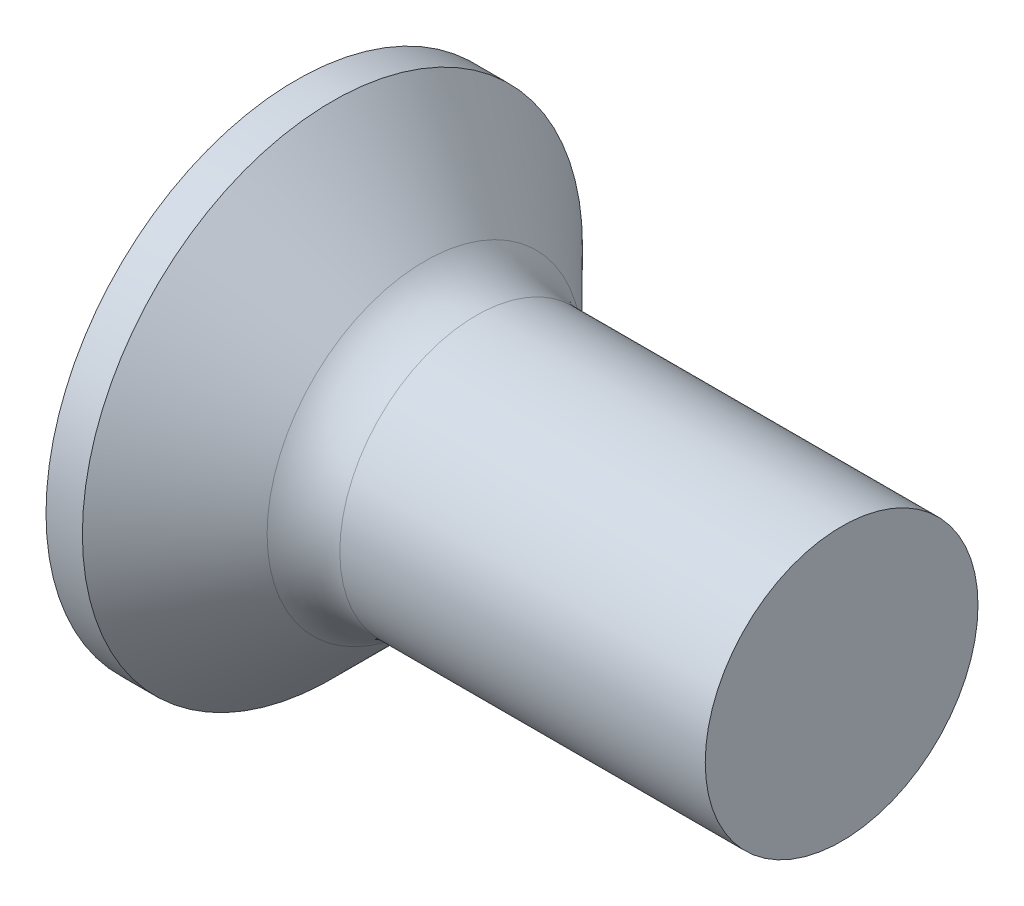
SolidWorks part; units mm, degrees
revolve "Base-Revolve" add sketch "BodySke"
sketch "BodySke" plane through (0, 0, 0) normal (0, 0, 1) x (1, 0, 0)
  line L0 (0, 0) -> (0, 2.75)
  line L1 (0, 2.75) -> (0.4, 2.75)
  line L2 (1.65, 1.5) -> (6, 1.5)
  line L3 (6, 1.5) -> (6, 0)
  line L4 (6, 0) -> (0, 0)
  line L5 (-6.35, 0) -> (82.55, 0) construction
  line L6 (1.65, -1.5) -> (6, -1.5) construction
  line L7 (0.4, -2.75) -> (1.65, -1.5) construction
  line L8 (0.4, 2.75) -> (1.65, 1.5)
  line L9 (0, -2.75) -> (0.4, -2.75) construction
  line L10 (2.15, 3.0875) -> (2.15, -6.4375) construction
  line L11 (0, 6.35) -> (0, -3.175) construction
  dimension "Diameter" = 3
  dimension "Head_ht" = 1.65
  dimension "Head_dia" = 5.5
  dimension "Head_ang" = 90
  dimension "D6" = 0.4
  dimension "Advance" = 0.5
cosmetic thread "ThreadCosmetic" [suppressed]
fillet "Fillet1" radius 0.8 1 edges at (1.65, 0, 1.5)
ref_plane "Plane1" through (0, 0, 0) normal (0, 0, 1) x (1, 0, 0)
ref_plane "Plane2" through (0, 0, 0) normal (0, 1, 0) x (1, 0, 0)
ref_plane "Plane3" through (0, 0, 0) normal (1, 0, 0) x (0, 0, -1)
sketch "Sketch3" plane through (0, 0, 0) normal (-1, 0, 0) x (0, 0, 1)
  line L0 (-0.37, 1.5) -> (0.37, 1.5)
  line L1 (0.37, 1.5) -> (0.37, -1.5)
  line L2 (0.37, -1.5) -> (-0.37, -1.5)
  line L3 (-0.37, -1.5) -> (-0.37, 1.5)
  dimension "Cross_dia" = 3
  dimension "Cross_width" = 0.74
  dimension "D1" = 1.5
  dimension "D2" = 0.37
ref_plane "Plane4" through (2.01, 0, 0) normal (-1, 0, 0) x (0, 0, 1)
sketch "Sketch4" plane through (2.01, 0, 0) normal (-1, 0, 0) x (0, 0, 1)
  line L0 (-0.37, 0.4979) -> (0.37, 0.4979)
  line L3 (0.37, 0.4979) -> (0.37, -0.4979)
  line L4 (0.37, -0.4979) -> (-0.37, -0.4979)
  line L5 (-0.37, -0.4979) -> (-0.37, 0.4979)
  dimension "D2" = 0.9957
  dimension "D1" = 0.74
  dimension "D4" = 0.4979
  dimension "D3" = 0.37
loft "Recess" cut profiles "Sketch3", "Sketch4"
pattern_circular "RecPat" count 2 every 90 about axis through (0, 0, 0) along (1, 0, 0) of "Recess"
sketch "RecCorSke" plane through (0, 0, 0) normal (0, 0, 1) x (1, 0, 0)
  line L0 (-3.175, 0) -> (15.875, 0) construction
  line L2 (0, 0) -> (0, 0.6966)
  line L3 (0, 0.6966) -> (2.01, 0.556)
  line L4 (2.01, 0.556) -> (2.1907, 0)
  line L5 (2.1907, 0) -> (0, 0)
  dimension "Diameter" = 1.112
  dimension "Depth" = 2.01
  dimension "Draft_angle" = 4
  dimension "Bottom_angle" = 18
revolve "RecessCore" cut sketch "RecCorSke" angle 360 about L0
sketch "ThdSchSke" plane through (0, 0, 0) normal (0, 0, 1) x (1, 0, 0)
  line L0 (2.15, -1.2195) -> (1.9536, -1.5)
  line L1 (2.15, -1.2195) -> (2.3464, -1.5)
  line L2 (2.3464, -1.5) -> (2.3464, -1.875)
  line L3 (-3.175, 0) -> (5.1513, 0) construction
  line L5 (2.3464, -1.875) -> (1.9536, -1.875)
  line L6 (1.9536, -1.875) -> (1.9536, -1.5)
  line L7 (0, 2.75) -> (0, -2.75) construction
  dimension "Diameter" = 3
  dimension "Thread_minor" = 2.439
  dimension "Start" = 2.15
revolve "ThreadSchematic" [suppressed] cut sketch "ThdSchSke" angle 360 about L3
pattern_linear "ThdSchPat" [suppressed]
equation "\"D1@Sketch3\" = \"Cross_dia@Sketch3\" / 2"
equation "\"D2@Sketch3\" = \"Cross_width@Sketch3\" / 2"
equation "\"Depth@RecCorSke\" = \"Cross_depth@Plane4\""
equation "\"D1@Sketch4\" = \"Cross_width@Sketch3\""
equation "\"D2@Sketch4\" = \"Cross_dia@Sketch3\" - 2.0 * \"Cross_depth@Plane4\" * tan(26.5  * 0.017453292)"
equation "\"D3@Sketch4\" = \"D1@Sketch4\" / 2"
equation "\"D4@Sketch4\" = \"D2@Sketch4\" / 2"
equation "\"Thread_length@ThreadCosmetic\" = ((sgn( (\"Length@BodySke\" - \"Advance@BodySke\" * 1.0 - \"Head_ht@BodySke\" ) - \"Thread_nom@BodySke\" )-1)*( (\"Length@BodySke\" - \"Advance@BodySke\" * 1.0 - \"Head_ht@BodySke\" ) - \"Thread_nom@BodySke\" ))/-2+ \"Thread_nom@BodySke\""
equation "\"Thread_minor@ThdSchSke\" = \"Thread_minor@ThreadCosmetic\""
equation "\"Diameter@ThdSchSke\" = \"Diameter@BodySke\""
equation "\"Overcut@ThdSchSke\" = \"Diameter@BodySke\" * 1.25"
equation "\"Start@ThdSchSke\" = 0.000001 + \"Length@BodySke\" - \"Thread_length@ThreadCosmetic\"  '---Countersunk---"
equation "\"Num_threads@ThdSchPat\" = int( \"Thread_length@ThreadCosmetic\" / \"Advance@BodySke\" + 0.999 )  + 1"
equation "\"Advance@ThdSchPat\" = \"Thread_length@ThreadCosmetic\" /  (\"Num_threads@ThdSchPat\" - 1) 'relax it"
